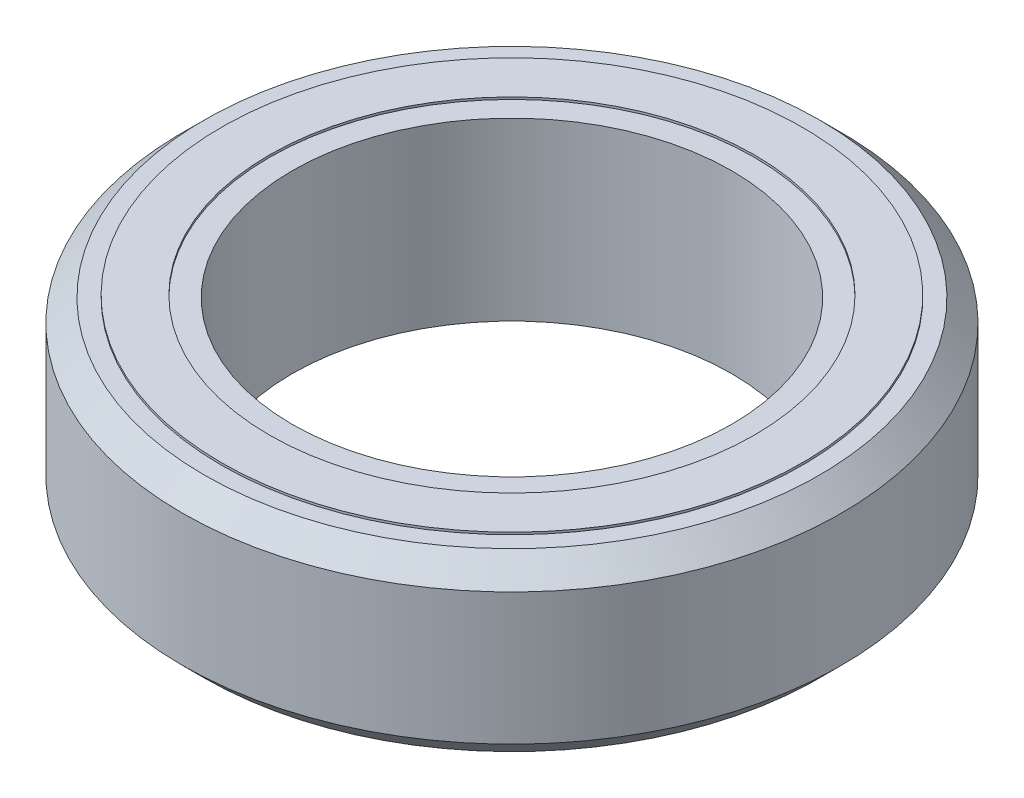
SolidWorks part; units mm, degrees
material "Acero aleado"
ref_plane "Alzado" through (0, 0, 0) normal (0, 0, 1) x (1, 0, 0)
ref_plane "Planta" through (0, 0, 0) normal (0, 1, 0) x (1, 0, 0)
ref_plane "Vista lateral" through (0, 0, 0) normal (1, 0, 0) x (0, 0, -1)
sketch "Croquis1" plane through (0, 0, 0) normal (0, 1, 0) x (1, 0, 0)
  circle A0 centre (0, 0) radius 5
  circle A1 centre (0, 0) radius 7.5
  dimension "D1" = 15
  dimension "D2" = 10
extrude "Saliente-Extruir1" add sketch "Croquis1" along normal mid plane 4
chamfer "Chaflán1" distance 0.5 angle 45 2 edges at (0, -2, 7.5) (0, 2, 7.5)
sketch "Croquis2" plane through (0, 0, 0) normal (0, 1, 0) x (1, 0, 0)
  circle A0 centre (0, 0) radius 5.5209
  circle A1 centre (0, 0) radius 6.6113
extrude "Saliente-Extruir2" add sketch "Croquis2" along normal mid plane 4.1
